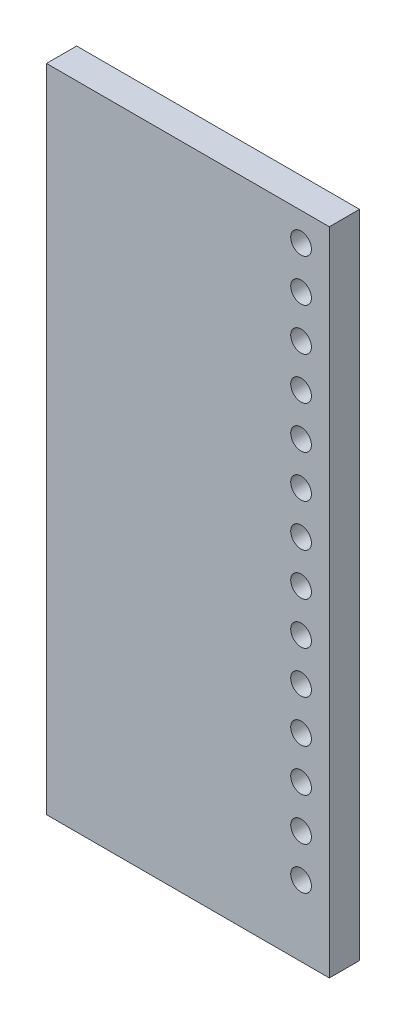
SolidWorks part; units mm, degrees
ref_plane "Front Plane" through (0, 0, 0) normal (0, 0, 1) x (1, 0, 0)
ref_plane "Top Plane" through (0, 0, 0) normal (0, 1, 0) x (1, 0, 0)
ref_plane "Right Plane" through (0, 0, 0) normal (1, 0, 0) x (0, 0, -1)
other "Bounding Box"
ref_plane "Default Plane" through (75, 0, 0) normal (-1, 0, 0) x (0, 0, 1)
sketch "Sketch1" plane through (0, 0, 0) normal (0, 0, 1) x (1, 0, 0)
  line L1 (-75, 0) -> (75, 0)
  line L2 (-75, 0) -> (-75, 345)
  line L3 (-75, 345) -> (75, 345)
  line L4 (75, 0) -> (75, 345)
  point P4 (0, 0)
  dimension "D1" = 150
  dimension "D2" = 345
extrude "Boss-Extrude1" add sketch "Sketch1" along normal blind 16
sketch "Sketch2" plane through (0, 0, 16) normal (0, 0, 1) x (1, 0, 0)
  line L0 (75, 0) -> (75, 37.5) construction
  line L1 (75, 0) -> (75, 345) construction
  line L2 (75, 37.5) -> (60, 37.5) construction
  line L3 (-75, 0) -> (75, 0) construction
  circle A0 centre (60, 37.5) radius 5.5
  dimension "D1" = 11
  dimension "D2" = 37.5
  dimension "D3" = 15
extrude "Cut-Extrude4" cut sketch "Sketch2" against normal through all
pattern_linear "LPattern1" count 14 spacing 22.5 along (0, 1, 0) of "Cut-Extrude4"
hole_wizard "#8-36 Tapped Hole1" positions "Sketch5" profile "Sketch4" tap size "#8-36" standard "ANSI Inch"
sketch "Sketch5" plane through (0, 0, 0) normal (0, -1, 0) x (-1, 0, 0)
  line L0 (-60, -8) -> (60, -8) construction
  line L2 (0, -8) -> (0, 14.7833) construction
  line L4 (-75, -16) -> (-75, 0) construction
  line L5 (75, -16) -> (75, 0) construction
  line L6 (75, -16) -> (-75, -16) construction
  line L7 (75, 0) -> (-75, 0) construction
  point P0 (-60, -8)
  point P2 (0, -8)
  point P4 (60, -8)
  dimension "D1" = 120
sketch "Sketch4" plane through (60, 0, 8) normal (1, 0, 0) x (0, 0, -1)
  line L0 (0, 0) -> (0, 26.0378)
  line L1 (0, 26.0378) -> (1.7272, 25)
  line L2 (1.7272, 25) -> (1.7272, 0)
  line L5 (1.7272, 0) -> (0, 0)
  line L10 (0, 26.0378) -> (-1.7272, 25) construction
  line L11 (0, -6.35) -> (0, 107.95) construction
  dimension "Tap Drill Dia." = 3.4544
  dimension "Tap Drill Depth" = 25
  dimension "Drill Angle" = 118
cosmetic thread "Hole Thread1"
cosmetic thread "Hole Thread2"
cosmetic thread "Hole Thread3"
